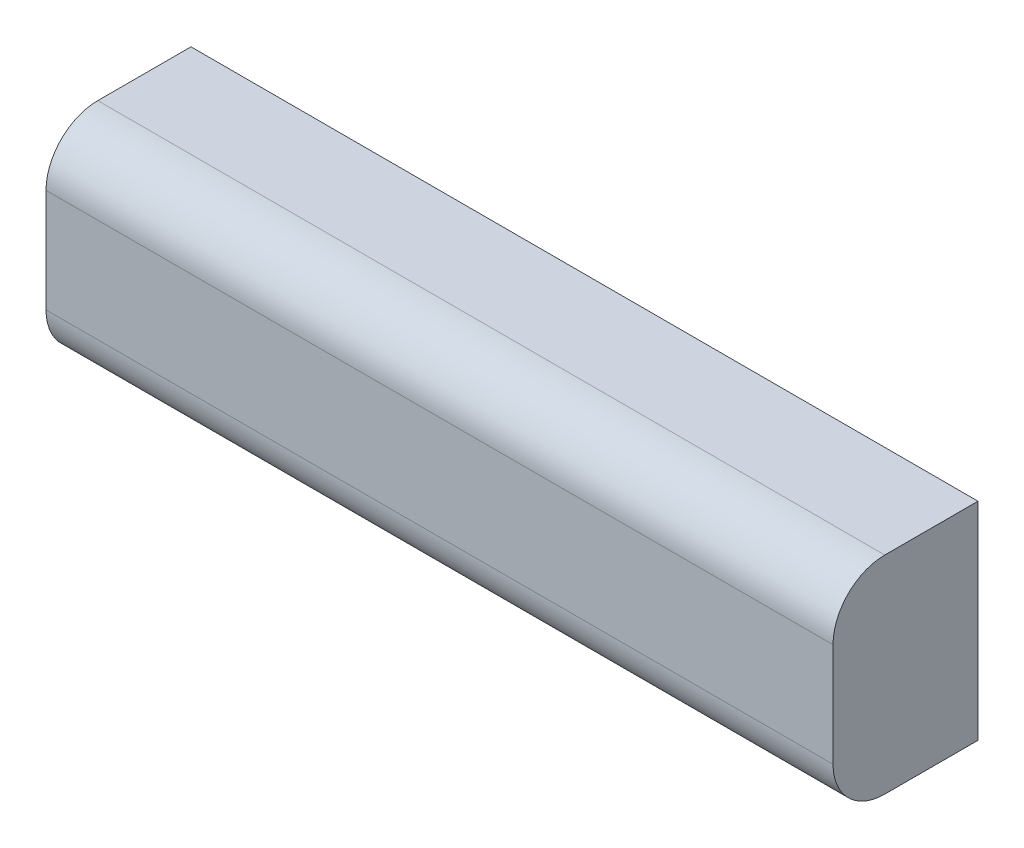
SolidWorks part; units mm, degrees
ref_plane "Front Plane" through (0, 0, 0) normal (0, 0, 1) x (1, 0, 0)
ref_plane "Top Plane" through (0, 0, 0) normal (0, 1, 0) x (1, 0, 0)
ref_plane "Right Plane" through (0, 0, 0) normal (1, 0, 0) x (0, 0, -1)
sketch "Sketch1" plane through (0, 0, 0) normal (1, 0, 0) x (0, 0, -1)
  line L1 (0, 0) -> (88.9, 0)
  line L2 (0, 0) -> (0, 127)
  line L3 (0, 127) -> (88.9, 127)
  line L4 (88.9, 0) -> (88.9, 127)
  dimension "D1" = 127
  dimension "D2" = 88.9
extrude "Boss-Extrude1" add sketch "Sketch1" along normal blind 482.6
fillet "Fillet2" radius 31.75 2 edges at (241.3, 0, 0) (241.3, 127, 0)
